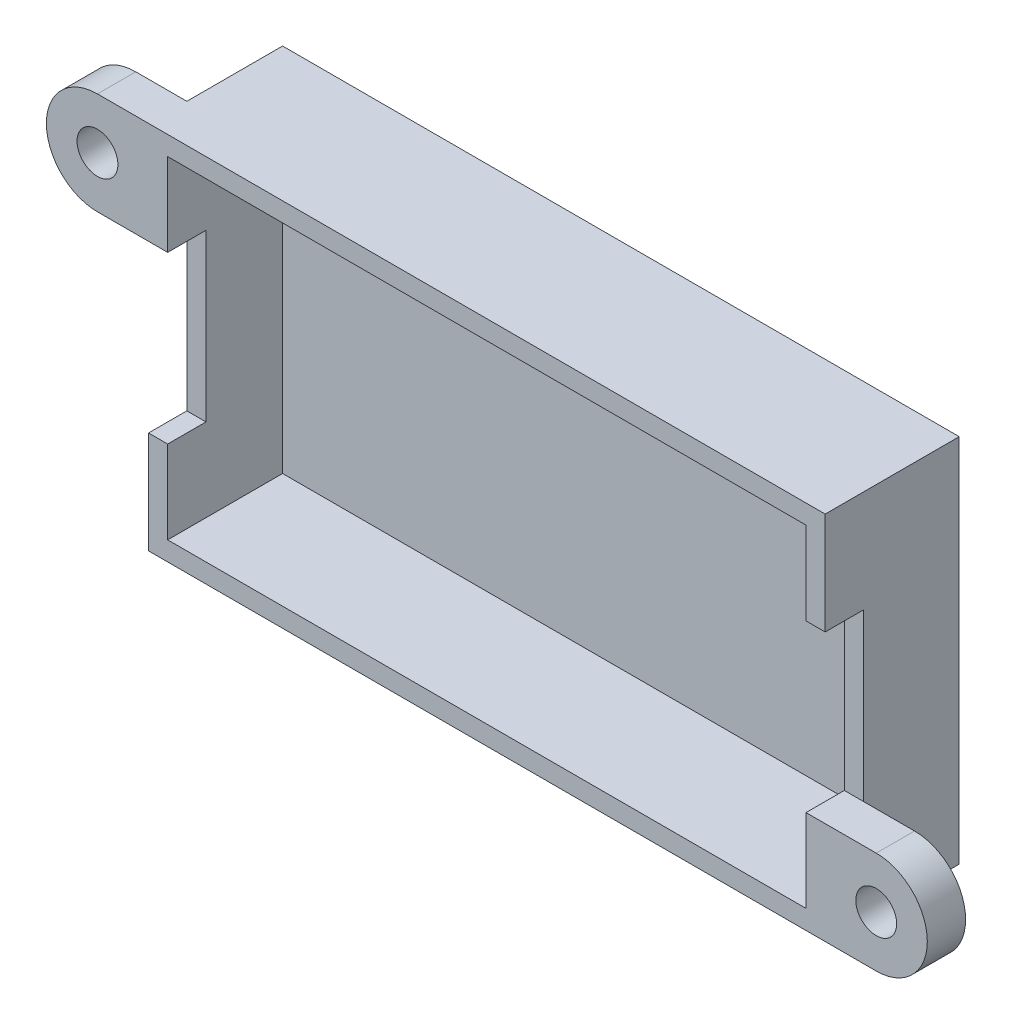
SolidWorks part; units mm, degrees
ref_plane "前视基准面" through (0, 0, 0) normal (0, 0, 1) x (1, 0, 0)
ref_plane "上视基准面" through (0, 0, 0) normal (0, 1, 0) x (1, 0, 0)
ref_plane "右视基准面" through (0, 0, 0) normal (1, 0, 0) x (0, 0, -1)
sketch "草图1" plane through (0, 0, 0) normal (0, 0, 1) x (1, 0, 0)
  line L1 (-26.5, -14.5) -> (26.5, -14.5)
  line L2 (-26.5, -14.5) -> (-26.5, 14.5)
  line L3 (-26.5, 14.5) -> (26.5, 14.5)
  line L4 (26.5, -14.5) -> (26.5, 14.5)
  line L5 (-26.5, -14.5) -> (26.5, 14.5) construction
  line L6 (-26.5, 14.5) -> (26.5, -14.5) construction
  point P0 (0, 0)
  dimension "D1" = 53
  dimension "D2" = 29
extrude "凸台-拉伸1" add sketch "草图1" along normal blind 10.5
shell "抽壳1" thickness 1.5
sketch "草图3" plane through (0, 0, 10.5) normal (0, 0, 1) x (1, 0, 0)
  line L0 (-26.5, 10.5) -> (-30.5, 10.5) construction
  line L1 (-26.5, 14.5) -> (-26.5, -14.5) construction
  line L2 (-26.5, 6.5) -> (-30.5, 6.5)
  line L3 (-26.5, 14.5) -> (-30.5, 14.5)
  line L4 (26.5, 14.5) -> (-26.5, 14.5) construction
  line L5 (-26.5, 14.5) -> (-26.5, 6.5)
  line L6 (26.5, -10.5) -> (30.5, -10.5) construction
  line L7 (26.5, -14.5) -> (26.5, 14.5) construction
  line L8 (26.5, -6.5) -> (30.5, -6.5)
  line L9 (26.5, -14.5) -> (30.5, -14.5)
  line L10 (-26.5, -14.5) -> (26.5, -14.5) construction
  line L11 (26.5, -6.5) -> (26.5, -14.5)
  arc A1 (-30.5, 14.5) -> (-30.5, 6.5) centre (-30.5, 10.5) ccw
  arc A3 (30.5, -14.5) -> (30.5, -6.5) centre (30.5, -10.5) ccw
  circle A4 centre (30.5, -10.5) radius 1.6
  circle A5 centre (-30.5, 10.5) radius 1.6
  point P4 (-28.5, 10.5)
  point P15 (28.5, -10.5)
  dimension "D7" = 3.2
  dimension "D8" = 3.2
  dimension "D1" = 8
  dimension "D2" = 4
  dimension "D3" = 0
  dimension "D4" = 4
  dimension "D5" = 8
  dimension "D6" = 0
extrude "凸台-拉伸2" add sketch "草图3" against normal blind 3
sketch "草图4" plane through (-26.5, 0, 0) normal (-1, 0, 0) x (0, 0, 1)
  line L0 (10.5, -14.5) -> (0, -14.5) construction
  line L1 (10.5, 6.5) -> (7.5, 6.5)
  line L2 (10.5, 6.5) -> (10.5, -6.5)
  line L3 (10.5, -6.5) -> (7.5, -6.5)
  line L4 (7.5, 6.5) -> (7.5, -6.5)
  dimension "D1" = 8
extrude "切除-拉伸1" cut sketch "草图4" against normal up to surface (53 mm away) up to face at (26.5, -2.1667, 6)
